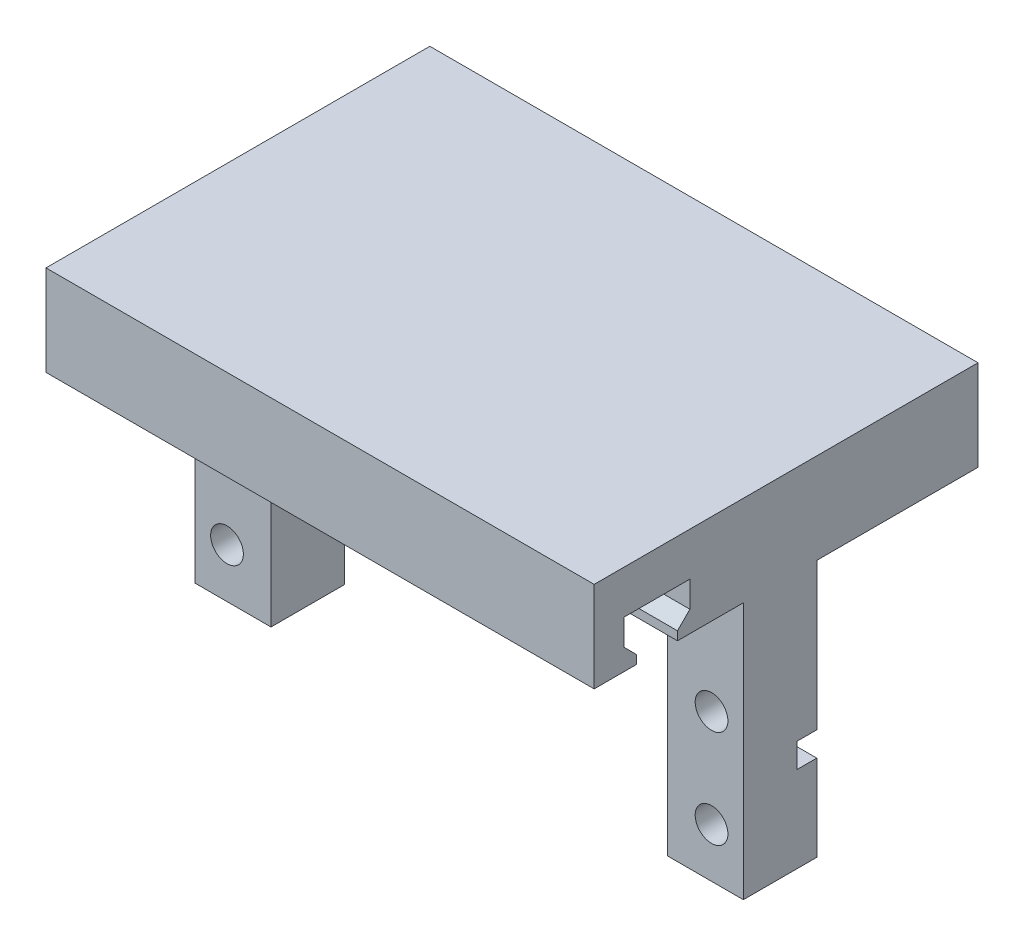
SolidWorks part; units mm, degrees
ref_plane "Ön Düzlem" through (0, 0, 0) normal (0, 0, 1) x (1, 0, 0)
ref_plane "Üst Düzlem" through (0, 0, 0) normal (0, 1, 0) x (1, 0, 0)
ref_plane "Sağ Düzlem" through (0, 0, 0) normal (1, 0, 0) x (0, 0, -1)
sketch "Sketch2" plane through (0, 0, 0) normal (1, 0, 0) x (0, 0, -1)
  line L0 (-39.25, 38.49) -> (-39.25, 29.24)
  line L1 (-34.9305, 29.24) -> (-39.25, 29.24)
  line L2 (-0.0386, 29.24) -> (-0.0386, 38.49)
  line L3 (-0.0386, 38.49) -> (-39.25, 38.49)
  line L4 (-34.9305, 29.24) -> (-34.9305, 30.129)
  line L5 (-34.9305, 30.129) -> (-36.2005, 31.399)
  line L6 (-36.2005, 31.399) -> (-36.2005, 34.066)
  line L7 (-36.2005, 34.066) -> (-29.4695, 34.066)
  line L8 (-29.4695, 34.066) -> (-29.4695, 31.399)
  line L9 (-29.4695, 31.399) -> (-30.7395, 30.129)
  line L10 (-30.7395, 30.129) -> (-30.7395, 29.24)
  line L11 (-30.7395, 29.24) -> (-0.0386, 29.24)
extrude "Boss-Extrude1" add sketch "Sketch2" along normal blind 56
sketch "Sketch3" plane through (56, 0, 0) normal (1, 0, 0) x (0, 0, -1)
  line L0 (-24.01, 29.24) -> (-16.51, 29.24)
  line L1 (-30.7395, 29.24) -> (-0.0386, 29.24) construction
  line L2 (-24.01, 29.24) -> (-24.01, 2.9693)
  line L3 (-24.01, 2.9693) -> (-16.51, 2.9693)
  line L5 (-16.51, 29.24) -> (-18.51, 29.24)
  line L7 (-18.51, 14.25) -> (-16.51, 14.25)
  line L8 (-18.51, 14.25) -> (-18.51, 11.75)
  line L9 (-18.51, 11.75) -> (-16.51, 11.75)
  line L10 (-16.51, 11.75) -> (-16.51, 2.9693)
  line L11 (-16.51, 29.24) -> (-16.51, 14.25)
  line M16 (-30.7395, 29.24) -> (-0.0386, 29.24)
  dimension "D1" = 7.5
  dimension "D2" = 26.2707
  dimension "D3" = 2
  dimension "D4" = 14.99
  dimension "D5" = 2.5
extrude "Boss-Extrude2" add sketch "Sketch3" against normal up to surface (56 mm away) contours L11 L0 L2 L3 L10 L9 L8 L7 M16 up to face at (0, 32.094, 28.4381)
sketch "Sketch4" plane through (0, 0, 24.01) normal (0, 0, 1) x (1, 0, 0)
  line L0 (0, 20.2237) -> (7.746, 20.2237)
  line L1 (0, 2.9693) -> (0, 29.24) construction
  line L2 (56, 20.8983) -> (48.254, 20.8983)
  line L3 (56, 29.24) -> (56, 2.9693) construction
  line L4 (26.1807, 29.24) -> (26.1807, 23.631)
  line L5 (56, 29.24) -> (0, 29.24) construction
  line L6 (26.1807, 23.631) -> (7.746, 23.631)
  line L7 (7.746, 23.631) -> (7.746, 7.5402)
  line L8 (26.1807, 23.631) -> (48.254, 23.631)
  line L9 (48.254, 23.631) -> (48.254, 2.9693)
  line L10 (0, 2.9693) -> (56, 2.9693) construction
  line L11 (48.254, 2.9693) -> (7.746, 2.9693)
  line L12 (7.746, 2.9693) -> (7.746, 7.5402)
  line M5 (0, 2.9693) -> (56, 2.9693)
  dimension "D1" = 7.746
  dimension "D2" = 7.746
  dimension "D3" = 5.609
extrude "Cut-Extrude1" cut sketch "Sketch4" against normal up to surface (7.5 mm away) contours L12 L9 L8 L6 L7 M5 up to face at (28, 21.745, 16.51)
sketch "Sketch5" plane through (0, 0, 24.01) normal (0, 0, 1) x (1, 0, 0)
  line L0 (3.5595, 29.24) -> (3.5595, 23.609)
  line L1 (0, 29.24) -> (56, 29.24) construction
  line L2 (5.1653, 29.24) -> (5.1653, 8.359)
  line L3 (56, 29.24) -> (0, 29.24) construction
  line L4 (5.1653, 8.359) -> (0, 8.359)
  line L5 (0, 2.9693) -> (0, 29.24) construction
  line L6 (0, 8.359) -> (0, 2.9693)
  line L7 (0, 2.9693) -> (7.746, 2.9693)
  line L8 (7.746, 2.9693) -> (7.746, 8.359)
  line L9 (7.746, 2.9693) -> (7.746, 23.631) construction
  line L10 (7.746, 8.359) -> (5.1653, 8.359)
  line L11 (48.254, 2.9693) -> (48.254, 8.359)
  line L12 (48.254, 23.631) -> (48.254, 2.9693) construction
  line L13 (48.254, 8.359) -> (56, 8.359)
  line L14 (56, 29.24) -> (56, 2.9693) construction
  line L15 (56, 8.359) -> (56, 2.9693)
  line L16 (56, 2.9693) -> (48.254, 2.9693)
  dimension "D1" = 5.631
  dimension "D2" = 20.881
sketch "Sketch6" plane through (0, 0, 24.01) normal (0, 0, 1) x (1, 0, 0)
  line L0 (3.25, 29.24) -> (3.25, 18)
  line L1 (0, 29.24) -> (56, 29.24) construction
  line L2 (0, 2.9693) -> (0, 29.24) construction
  line L3 (3.25, 18) -> (3.25, 8)
  line L4 (0, 29.24) -> (56, 29.24)
  line L5 (28, 29.24) -> (28, 13.0905)
  circle A0 centre (3.25, 18) radius 1.672
  circle A1 centre (3.25, 8) radius 1.672
  circle A2 centre (52.75, 18) radius 1.672
  circle A3 centre (52.75, 8) radius 1.672
  dimension "D3" = 3.344
  dimension "D4" = 3.344
  dimension "D6" = 3.344
  dimension "D1" = 11.24
  dimension "D2" = 3.25
  dimension "D5" = 10
  dimension "D7" = 56
extrude "Cut-Extrude4" cut sketch "Sketch6" against normal up to surface (7.5 mm away) up to face at (28, 20.3428, 16.51)
